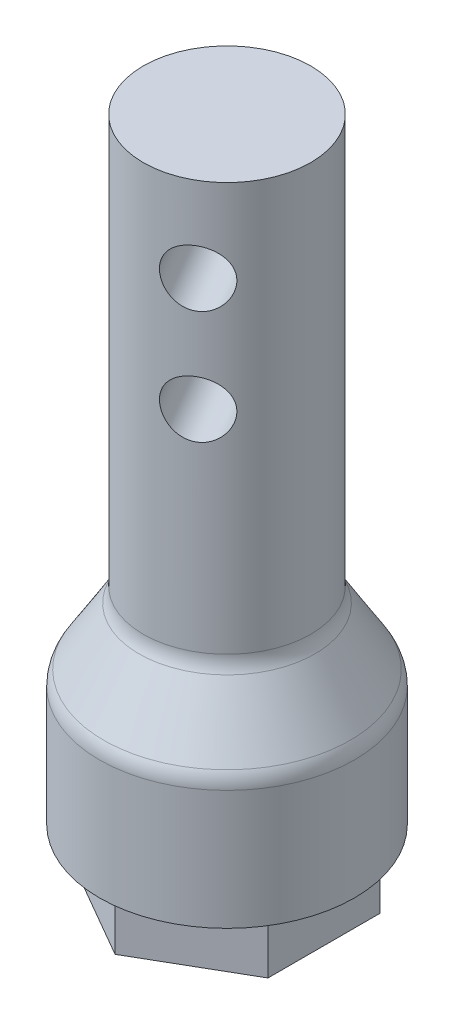
SolidWorks part; units mm, degrees
ref_plane "Piano frontale" through (0, 0, 0) normal (0, 0, 1) x (1, 0, 0)
ref_plane "Piano superiore" through (0, 0, 0) normal (0, 1, 0) x (1, 0, 0)
ref_plane "Piano destro" through (0, 0, 0) normal (1, 0, 0) x (0, 0, -1)
sketch "Schizzo1" plane through (0, 0, 0) normal (0, 0, 1) x (1, 0, 0)
  line L0 (0, 0) -> (4.5, 0)
  line L1 (4.5, 0) -> (4.5, 6.2159)
  line L2 (4.3507, 6.7416) -> (3.1043, 8.7584)
  line L3 (2.955, 9.2841) -> (2.955, 31.7)
  line L4 (2.955, 31.7) -> (0, 31.7)
  line L5 (0, 31.7) -> (0, 0) construction
  line L6 (0, 0) -> (0, 31.7)
  arc A0 (4.5, 6.2159) -> (4.3507, 6.7416) centre (3.5, 6.2159) ccw
  arc A1 (3.1043, 8.7584) -> (2.955, 9.2841) centre (3.955, 9.2841) cw
  point P9 (4.5, 6.5)
  point P12 (2.955, 9)
  dimension "D6" = 1
  dimension "D1" = 31.7
  dimension "D2" = 5.91
  dimension "D3" = 9
  dimension "D4" = 6.5
  dimension "D5" = 2.5
revolve "Rivoluzione1" add sketch "Schizzo1" angle 360 about L5
sketch "Schizzo2" plane through (0, 0, 0) normal (0, -1, 0) x (1, 0, 0)
  line L1 (0, 3.95) -> (-3.4208, 1.975)
  line L2 (-3.4208, 1.975) -> (-3.4208, -1.975)
  line L3 (-3.4208, -1.975) -> (0, -3.95)
  line L4 (0, -3.95) -> (3.4208, -1.975)
  line L5 (3.4208, -1.975) -> (3.4208, 1.975)
  line L6 (3.4208, 1.975) -> (0, 3.95)
  circle A0 centre (0, 0) radius 3.95 construction
  circle A2 centre (0, 0) radius 4.5 construction
  circle A3 centre (0, 0) radius 4.5
  dimension "D1" = 7.9
extrude "Taglio-Estrusione1" cut sketch "Schizzo2" against normal blind 2
hole_wizard "Foro filettato M3x0.5-1" positions "Schizzo4" profile "Schizzo3" tap size "M3x0.5" standard "Ansi Metric"
sketch "Schizzo4" plane through (0, 0, 0) normal (0, -1, 0) x (-1, 0, 0)
  point P0 (0, 0)
sketch "Schizzo3" plane through (0, 0, 0) normal (1, 0, 0) x (0, 0, -1)
  line L0 (0, 0) -> (0, 9.7511)
  line L1 (0, 9.7511) -> (1.25, 9)
  line L2 (1.25, 9) -> (1.25, 0)
  line L5 (1.25, 0) -> (0, 0)
  line L10 (0, 9.7511) -> (-1.25, 9) construction
  line L11 (0, -6.35) -> (0, 107.95) construction
  dimension "Tap Drill Dia." = 2.5
  dimension "Tap Drill Depth" = 9
  dimension "Drill Angle" = 118
cosmetic thread "Filettatura del foro1" parameters "D1"=9, "D2"=3
ref_plane "Piano1" through (-1.4775, 0, -2.5591) normal (-0.5, 0, -0.866) x (-0.866, 0, 0.5)
sketch "Schizzo5" plane through (-1.4775, 0, -2.5591) normal (-0.5, 0, -0.866) x (-0.866, 0, 0.5)
  line L0 (0, 28.7) -> (0, 9.2841) construction
  line L1 (2.955, 9.2841) -> (-2.955, 9.2841) construction
  line L2 (2.955, 31.7) -> (-2.955, 31.7) construction
  circle A0 centre (0, 16.7) radius 1
  circle A1 centre (0, 20.7) radius 1
  circle A2 centre (0, 24.7) radius 1
  circle A3 centre (0, 28.7) radius 1
  dimension "D1" = 2
  dimension "D2" = 12
  dimension "D3" = 4
  dimension "D4" = 4
  dimension "D5" = 3
extrude "Taglio-Estrusione2" cut sketch "Schizzo5" against normal through all
ref_plane "Piano2" through (0, 23.7, 0) normal (0, 1, 0) x (1, 0, 0)
other "TaglioSuperficie1"
